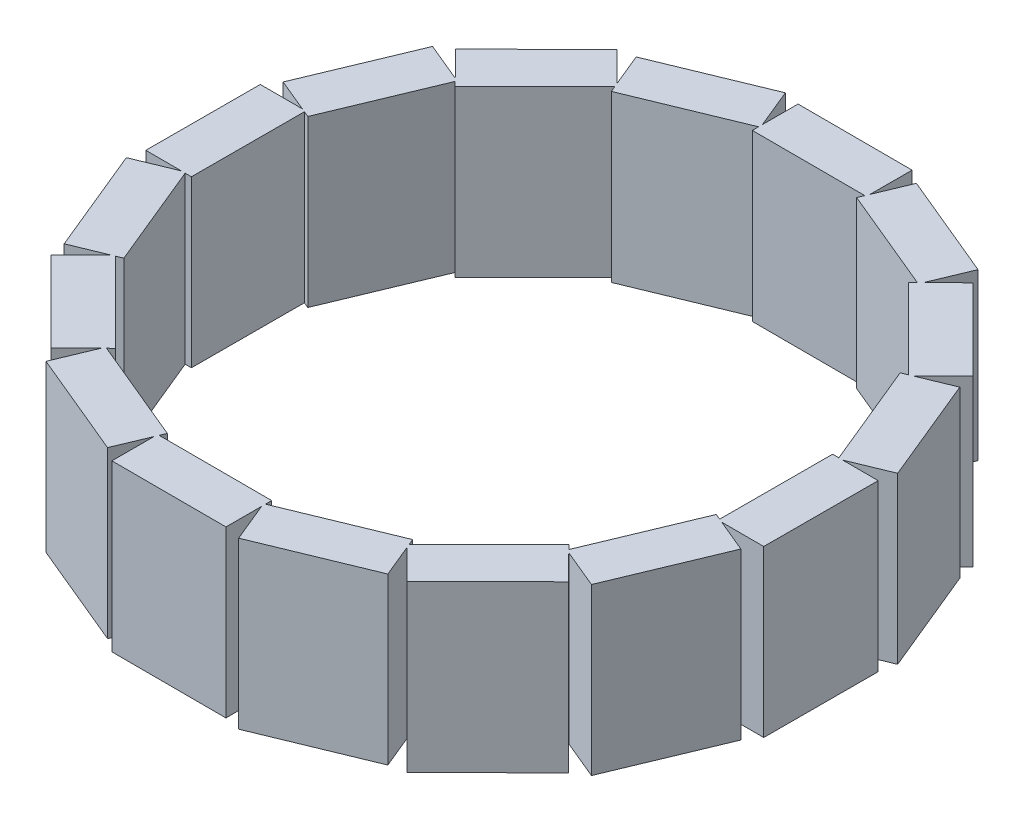
SolidWorks part; units mm, degrees
ref_plane "Front Plane" through (0, 0, 0) normal (0, 0, 1) x (1, 0, 0)
ref_plane "Top Plane" through (0, 0, 0) normal (0, 1, 0) x (1, 0, 0)
ref_plane "Right Plane" through (0, 0, 0) normal (1, 0, 0) x (0, 0, -1)
sketch "Sketch1" plane through (0, 0, 0) normal (0, 1, 0) x (1, 0, 0)
  circle A0 centre (0, 0) radius 140.65
  dimension "D1" = 281.3
extrude "Boss-Extrude1" add sketch "Sketch1" along normal blind 12.7
sketch "Sketch3" plane through (0, 12.7, 0) normal (0, 1, 0) x (1, 0, 0)
  line L0 (-62.5125, 104.7329) -> (-16.283, 123.7811)
  line L1 (-16.283, 123.7811) -> (-23.9023, 142.2729)
  line L2 (-23.9023, 142.2729) -> (-70.1318, 123.2247)
  line L3 (-70.1318, 123.2247) -> (-62.5125, 104.7329)
  circle A0 centre (0, 0) radius 140.65 construction
  dimension "D1" = 50
  dimension "D2" = 20
extrude "Boss-Extrude2" add sketch "Sketch3" along normal blind 72.4
pattern_circular "CirPattern1" count 16 over 360 about axis through (0.6788, 0, 1.9151) along (0, 1, 0) of "Boss-Extrude2"
sketch "Sketch4" plane through (0, 0, 0) normal (0, -1, 0) x (1, 0, 0)
  circle A0 centre (0, 0) radius 140.65
  dimension "D1" = 281.3
extrude "Cut-Extrude1" cut sketch "Sketch4" against normal blind 12.7
